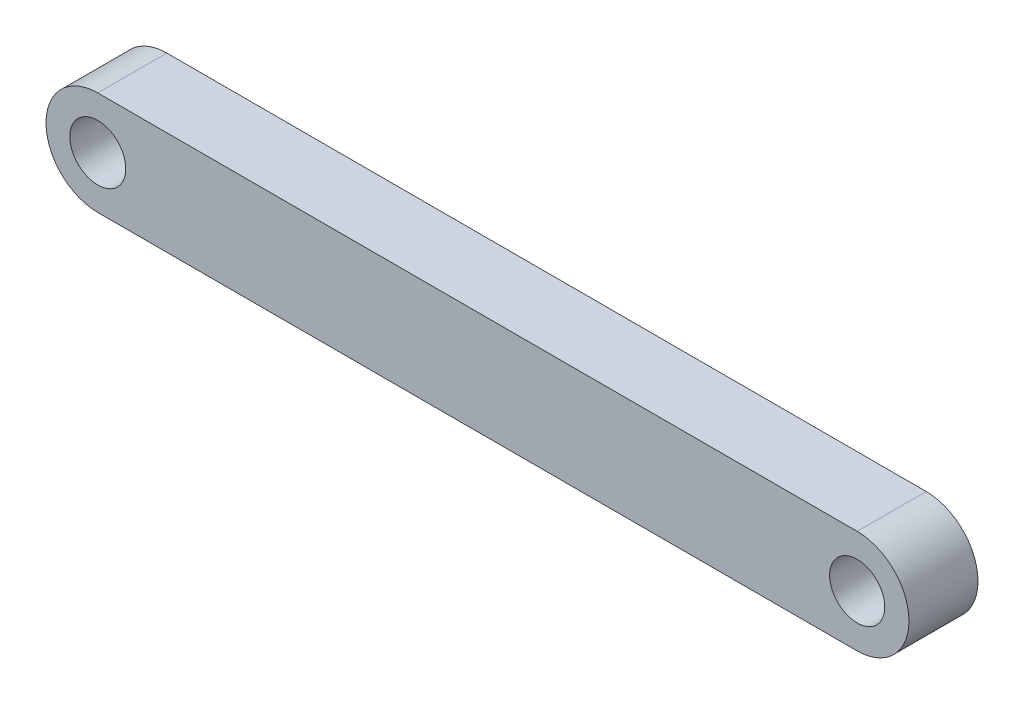
SolidWorks part; units mm, degrees
ref_plane "Alzado" through (0, 0, 0) normal (0, 0, 1) x (1, 0, 0)
ref_plane "Planta" through (0, 0, 0) normal (0, 1, 0) x (1, 0, 0)
ref_plane "Vista lateral" through (0, 0, 0) normal (1, 0, 0) x (0, 0, -1)
sketch "Croquis1" plane through (0, 0, 0) normal (0, 0, 1) x (1, 0, 0)
  line L0 (55, 0) -> (-55, 0) construction
  line L1 (-55, 0) -> (55, 0) construction
  line L2 (-55, 7.5) -> (55, 7.5)
  line L3 (-55, -7.5) -> (55, -7.5)
  circle A0 centre (-55, 0) radius 4.0526
  circle A1 centre (55, 0) radius 3.9919
  arc A2 (-55, 7.5) -> (-55, -7.5) centre (-55, 0) ccw
  arc A3 (55, -7.5) -> (55, 7.5) centre (55, 0) ccw
  point P4 (0, 0)
  point P6 (0, 0)
  dimension "D2" = 7.5
  dimension "D1" = 110
extrude "Saliente-Extruir1" add sketch "Croquis1" along normal blind 10
